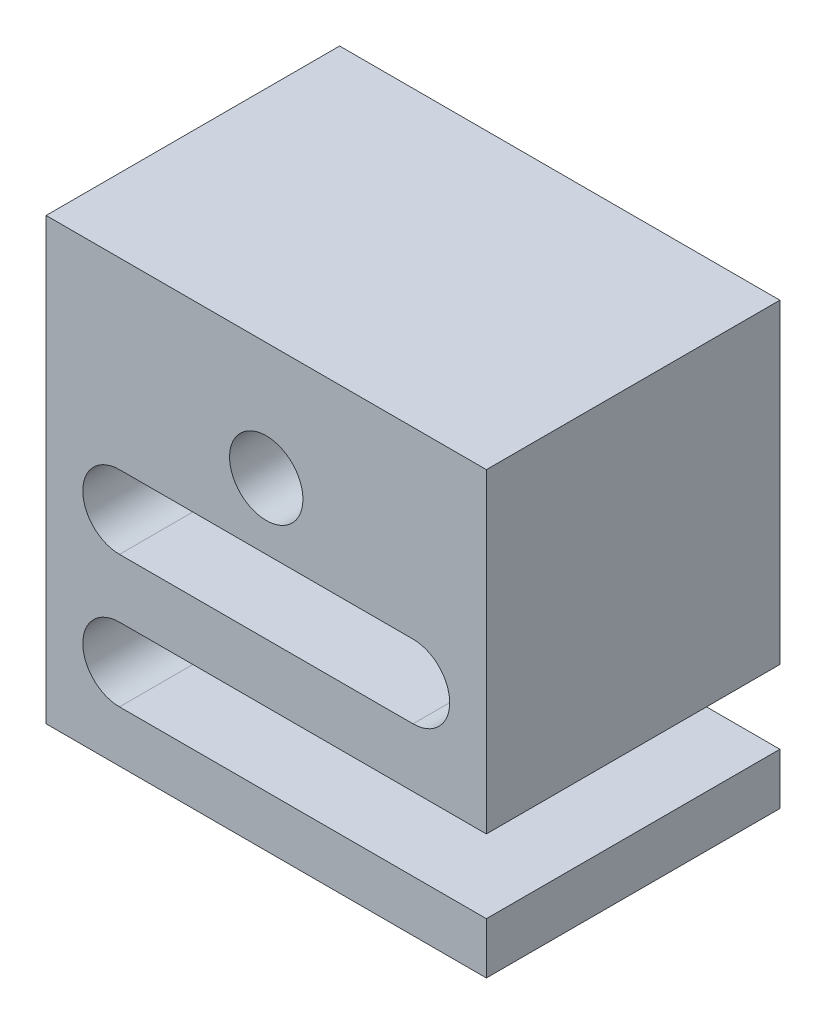
SolidWorks part; units mm, degrees
ref_plane "Front Plane" through (0, 0, 0) normal (0, 0, 1) x (1, 0, 0)
ref_plane "Top Plane" through (0, 0, 0) normal (0, 1, 0) x (1, 0, 0)
ref_plane "Right Plane" through (0, 0, 0) normal (1, 0, 0) x (0, 0, -1)
sketch "Sketch1" plane through (0, 0, 0) normal (0, 0, 1) x (1, 0, 0)
  line L1 (-19.05, -19.05) -> (19.05, -19.05)
  line L2 (-19.05, -19.05) -> (-19.05, 19.05)
  line L3 (-19.05, 19.05) -> (19.05, 19.05)
  line L4 (19.05, -19.05) -> (19.05, 19.05)
  line L5 (-19.05, -19.05) -> (19.05, 19.05) construction
  line L6 (-19.05, 19.05) -> (19.05, -19.05) construction
  point P0 (0, 0)
  dimension "D1" = 38.1
  dimension "D2" = 38.1
extrude "Boss-Extrude1" add sketch "Sketch1" along normal mid plane 25.4
sketch "Sketch2" plane through (0, 0, 12.7) normal (0, 0, 1) x (1, 0, 0)
  line L0 (-12.7, -11.43) -> (19.05, -11.43) construction
  line L1 (-12.7, -8.255) -> (19.05, -8.255)
  line L2 (-12.7, -14.605) -> (19.05, -14.605)
  line L3 (19.05, -19.05) -> (19.05, 19.05) construction
  line L4 (-19.05, -19.05) -> (19.05, -19.05) construction
  line L5 (13.97, 0) -> (-13.97, 0) construction
  arc A0 (-12.7, -8.255) -> (-12.7, -14.605) centre (-12.7, -11.43) ccw
  arc A1 (19.05, -14.605) -> (19.05, -8.255) centre (19.05, -11.43) ccw
  point P2 (3.175, -11.43)
  point P7 (0, 0)
  dimension "D1" = 6.35
  dimension "D2" = 31.75
  dimension "D3" = 7.62
extrude "Cut-Extrude1" cut sketch "Sketch2" against normal blind 25.4
sketch "Sketch3" plane through (0, 0, 12.7) normal (0, 0, 1) x (1, 0, 0)
  line L0 (0, -13.97) -> (0, 13.97) construction
  line L1 (19.05, 19.05) -> (-19.05, 19.05) construction
  point P0 (0, 8.89)
  point P1 (0, 0)
  point P2 (0, 0)
  point P3 (0, 0)
  dimension "D1" = 10.16
hole_wizard "1/4 (0.25) Diameter Hole1" positions "Sketch4" profile "Sketch6" hole size "1/4" standard "ANSI Inch" end condition through all
sketch "Sketch4" plane through (0, 0, 12.7) normal (0, 0, 1) x (1, 0, 0)
  point P0 (0, 8.89)
sketch "Sketch6" plane through (0, 8.89, 12.7) normal (1, 0, 0) x (0, -1, 0)
  line L0 (0, 0) -> (0, 25.4)
  line L1 (0, 25.4) -> (3.175, 25.4)
  line L2 (3.175, 25.4) -> (3.175, 0)
  line L5 (3.175, 0) -> (0, 0)
  line L11 (0, -6.35) -> (0, 107.95) construction
  dimension "Thru Hole Dia." = 6.35
  dimension "Thru Hole Depth" = 25.4
sketch "Sketch7" plane through (0, 0, 12.7) normal (0, 0, 1) x (1, 0, 0)
  line L0 (-12.7, 0) -> (12.7, 0) construction
  line L1 (13.97, 0) -> (-13.97, 0) construction
  line L2 (-12.7, 3.175) -> (12.7, 3.175)
  line L3 (-12.7, -3.175) -> (12.7, -3.175)
  arc A0 (-12.7, 3.175) -> (-12.7, -3.175) centre (-12.7, 0) ccw
  arc A1 (12.7, -3.175) -> (12.7, 3.175) centre (12.7, 0) ccw
  point P5 (0, 0)
  point P10 (0, 0)
  point P12 (0, 0)
  dimension "D1" = 6.35
  dimension "D2" = 25.4
extrude "Cut-Extrude2" cut sketch "Sketch7" against normal blind 25.4
